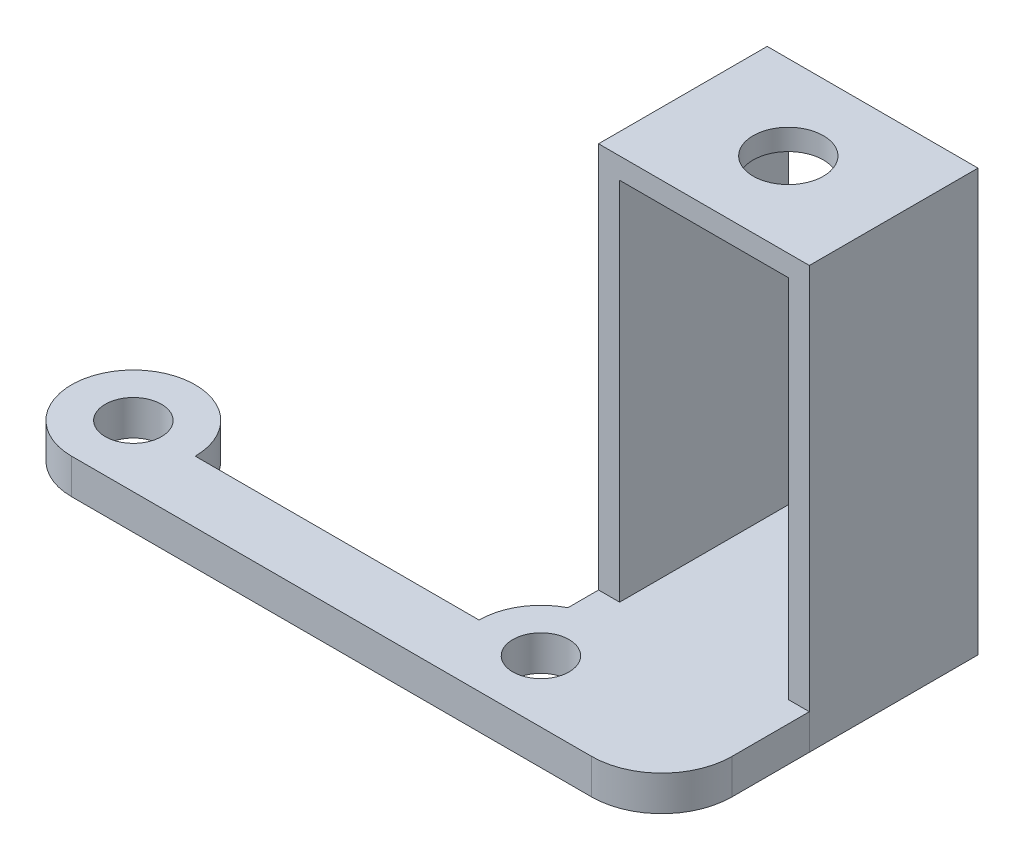
SolidWorks part; units mm, degrees
material "5052-H32"
ref_plane "正面" through (0, 0, 0) normal (0, 0, 1) x (1, 0, 0)
ref_plane "平面" through (0, 0, 0) normal (0, 1, 0) x (1, 0, 0)
ref_plane "右側面" through (0, 0, 0) normal (1, 0, 0) x (0, 0, -1)
sketch "ｽｹｯﾁ1" plane through (0, 0, 0) normal (0, 1, 0) x (1, 0, 0)
  line L0 (-29, 0) -> (29, 0) construction
  line L11 (-20.2, 0) -> (20.2, 0)
  line L13 (-29, -8.8) -> (29, -8.8)
  circle A0 centre (-29, 0) radius 4
  circle A1 centre (29, 0) radius 4
  arc A4 (-20.2, 0) -> (-29, -8.8) centre (-29, 0) ccw
  arc A6 (29, -8.8) -> (20.2, 0) centre (29, 0) ccw
  point P15 (-37.2627, -3.0278)
  dimension "D2" = 8
  dimension "D3" = 8.8
  dimension "D1" = 8
  dimension "D5" = 8.8
  dimension "D6" = 58
extrude "ﾎﾞｽ - 押し出し1" add sketch "ｽｹｯﾁ1" along normal blind 5
sketch "ｽｹｯﾁ2" plane through (0, 0, 0) normal (0, 1, 0) x (1, 0, 0)
  line L0 (-29, -8.8) -> (29, -8.8) construction
  line L1 (29, -8.8) -> (55, -8.8)
  line L2 (25, 7.8384) -> (25, 12.2)
  line L3 (28, 36.2) -> (52, 36.2)
  line L4 (55, -8.8) -> (55, 12.2)
  line L9 (25, 12.2) -> (28, 12.2)
  line L11 (52, 12.2) -> (52, 36.2)
  line L12 (52, 12.2) -> (55, 12.2)
  line L14 (25, 36.2) -> (55, 36.2) construction
  line L15 (55, -8.8) -> (55, 36.2) construction
  line L16 (52, -8.8) -> (52, 36.2) construction
  line L17 (28, 12.2) -> (28, 36.2)
  line L18 (25, 12.2) -> (55, 12.2) construction
  arc A2 (29, -8.8) -> (20.2, 0) centre (29, 0) ccw construction
  arc A3 (29, -8.8) -> (25, 7.8384) centre (29, 0) ccw
  point P16 (25, 7.8384)
  dimension "D1" = 30
  dimension "D2" = 45
  dimension "D6" = 4
  dimension "D4" = 3
  dimension "D3" = 24
  dimension "D5" = 3
extrude "ﾎﾞｽ - 押し出し2" add sketch "ｽｹｯﾁ2" along normal up to surface (5 mm away) up to face at (-29, 5, 4)
sketch "ｽｹｯﾁ5" plane through (0, 0, -12.2) normal (0, 0, -1) x (-1, 0, 0)
  line L0 (-52, 5) -> (-52, 0) construction
  line L1 (-55, 0) -> (-52, 0)
  line L2 (-55, 0) -> (-55, 60)
  line L3 (-55, 60) -> (-25, 60)
  line L4 (-25, 0) -> (-25, 60)
  line L5 (-28, 5) -> (-28, 0) construction
  line L6 (-52, 57) -> (-52, 0)
  line L7 (-28, 57) -> (-28, 0)
  line L8 (-28, 0) -> (-25, 0)
  line L9 (-52, 57) -> (-28, 57)
  line L11 (-55, 57) -> (-25, 57) construction
  dimension "D2" = 60
  dimension "D1" = 3
extrude "ﾎﾞｽ - 押し出し3" add sketch "ｽｹｯﾁ5" along normal up to surface (24 mm away) separate body up to face at (40, 2.5, -36.2)
sketch "ｽｹｯﾁ6" plane through (0, 57, 0) normal (0, -1, 0) x (1, 0, 0)
  line L0 (28, -12.2) -> (52, -36.2) construction
  circle A0 centre (40, -24.2) radius 5
  dimension "D1" = 10
extrude "ｶｯﾄ - 押し出し1" cut sketch "ｽｹｯﾁ6" against normal blind 5
fillet "ﾌｨﾚｯﾄ1" radius 10 1 edges at (55, 2.5, 8.8)
